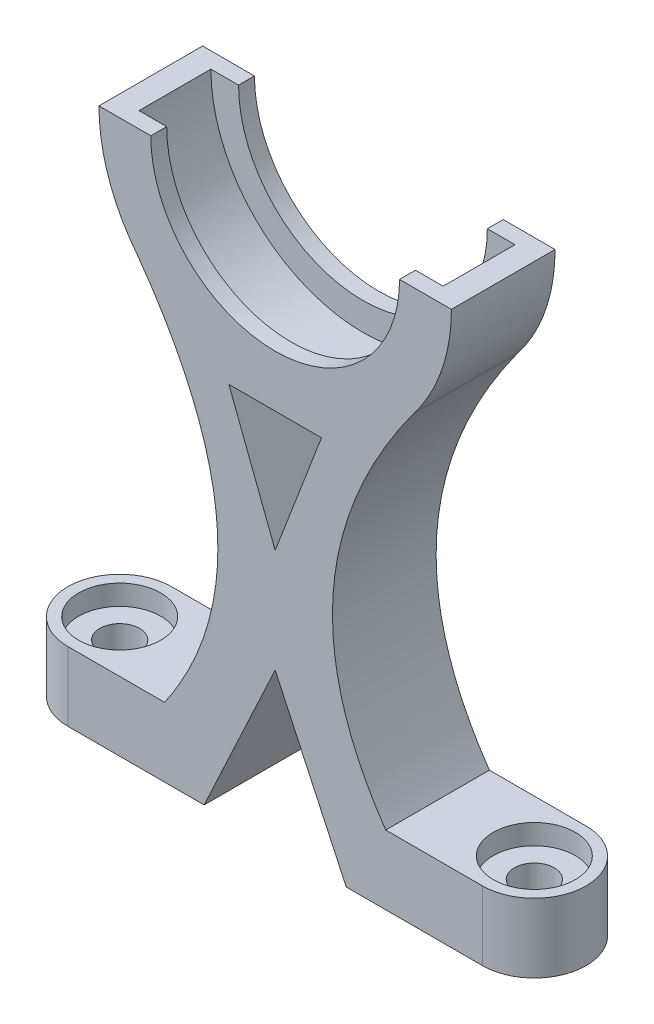
SolidWorks part; units mm, degrees
material "ABS"
ref_plane "Front Plane" through (0, 0, 0) normal (0, 0, 1) x (1, 0, 0)
ref_plane "Top Plane" through (0, 0, 0) normal (0, 1, 0) x (1, 0, 0)
ref_plane "Right Plane" through (0, 0, 0) normal (1, 0, 0) x (0, 0, -1)
sketch "Sketch1" plane through (0, 0, 0) normal (0, 0, 1) x (1, 0, 0)
  line L2 (0, -11.43) -> (0, -50.8) construction
  line L3 (6.5273, -50.8) -> (0, -36.8021)
  line L4 (-19.05, -50.8) -> (-6.5273, -50.8)
  line L5 (-6.5273, -50.8) -> (0, -36.8021)
  line L6 (-19.05, -44.45) -> (-10.16, -44.45)
  line L8 (4.255, -16.1925) -> (-4.255, -16.1925)
  line L9 (-4.255, -16.1925) -> (0, -27.2771)
  line L10 (19.05, -50.8) -> (6.5273, -50.8)
  line L11 (19.05, -44.45) -> (10.16, -44.45)
  line L12 (4.255, -16.1925) -> (0, -27.2771)
  line L13 (-16.1925, 0) -> (-11.43, 0)
  line L14 (11.43, 0) -> (16.1925, 0)
  line L15 (-19.05, -44.45) -> (-19.05, -50.8)
  line L16 (19.05, -44.45) -> (19.05, -50.8)
  arc A0 (-11.43, 0) -> (0, -11.43) centre (0, 0) ccw construction
  arc A1 (-11.43, 0) -> (11.43, 0) centre (0, 0) ccw
  arc A2 (-16.1925, 0) -> (-12.7, -10.0453) centre (0, 0) ccw
  arc A7 (16.1925, 0) -> (12.7, -10.0453) centre (0, 0) cw
  spline S0 degree 2 poles (-12.7, -10.0453) (0.7677, -28.6515) (-10.16, -44.45) knots 0 0 0 1 1 1
  spline S1 degree 2 poles (12.7, -10.0453) (-0.7677, -28.6515) (10.16, -44.45) knots 0 0 0 1 1 1
  point P1 (-19.05, -47.625)
  point P30 (0, -16.1925)
  dimension "D2" = 4.7625
  dimension "D9" = 4.255
  dimension "D10" = 44.45
  dimension "D11" = 11.43
  dimension "D3" = 12.7
  dimension "D4" = 19.05
  dimension "D5" = 8.89
  dimension "D6" = 12.7
  dimension "D7" = 50.8
  dimension "D8" = 25
  dimension "D12" = 9.525
  dimension "D13" = 69
extrude "Boss-Extrude1" add sketch "Sketch1" along normal mid plane 9.525
sketch "Sketch4" plane through (0, 0, 0) normal (1, 0, 0) x (0, 0, -1)
  line L0 (0, 0) -> (0, -12.7) construction
  line L2 (0, 0) -> (13.5373, 0) construction
  line L3 (-3.302, -13.97) -> (3.302, -13.97)
  line L4 (-3.302, -13.97) -> (-3.302, -11.43)
  line L5 (-3.302, -11.43) -> (3.302, -11.43)
  line L6 (3.302, -13.97) -> (3.302, -11.43)
  line L7 (-3.302, -13.97) -> (3.302, -11.43) construction
  line L8 (-3.302, -11.43) -> (3.302, -13.97) construction
  dimension "D1" = 11.43
  dimension "D2" = 6.604
  dimension "D3" = 2.54
revolve "Cut-Revolve1" cut sketch "Sketch4" angle 360 about L2
sketch "Sketch8" plane through (0, -44.45, 0) normal (0, 1, 0) x (1, 0, 0)
  line L2 (0, 0) -> (0, -1.6622) construction
  line L3 (-19.05, -4.7625) -> (-19.05, 4.7625) construction
  line L4 (19.05, -4.7625) -> (19.05, 4.7625) construction
  line L5 (-19.05, 4.7625) -> (-19.05, -4.7625)
  line L6 (19.05, 4.7625) -> (19.05, -4.7625)
  arc A0 (-19.05, 4.7625) -> (-19.05, -4.7625) centre (-19.05, 0) ccw
  arc A1 (19.05, -4.7625) -> (19.05, 4.7625) centre (19.05, 0) ccw
extrude "Boss-Extrude2" add sketch "Sketch8" against normal blind 6.35
hole_wizard "CBORE for #6 Button Head Cap Screw1" positions "Sketch5" profile "Sketch6" counterbore size "#6" standard "ANSI Inch"
sketch "Sketch5" plane through (0, -44.45, 0) normal (0, 1, 0) x (1, 0, 0)
  point P32 (-19.05, 0)
  point P34 (19.05, 0)
sketch "Sketch6" plane through (-19.05, -44.45, 0) normal (1, 0, 0) x (0, 0, 1)
  line L0 (0, 0) -> (0, 6.35)
  line L1 (0, 6.35) -> (1.8288, 6.35)
  line L3 (1.8288, 6.35) -> (1.8288, 1.8542)
  line L4 (1.8288, 1.8542) -> (3.7706, 1.8542)
  line L5 (3.7706, 1.8542) -> (3.7706, 0)
  line L7 (3.7706, 0) -> (0, 0)
  line L11 (0, -6.35) -> (0, 107.95) construction
  dimension "Thru Hole Dia." = 3.6576
  dimension "Thru Hole Depth" = 6.35
  dimension "C'Bore Dia." = 7.5413
  dimension "C'Bore Depth" = 1.8542
fillet "Fillet2" [suppressed] radius 1.27
fillet "Fillet3" [suppressed] radius 0.254
equation "\"pWidth\"= 0.375"
